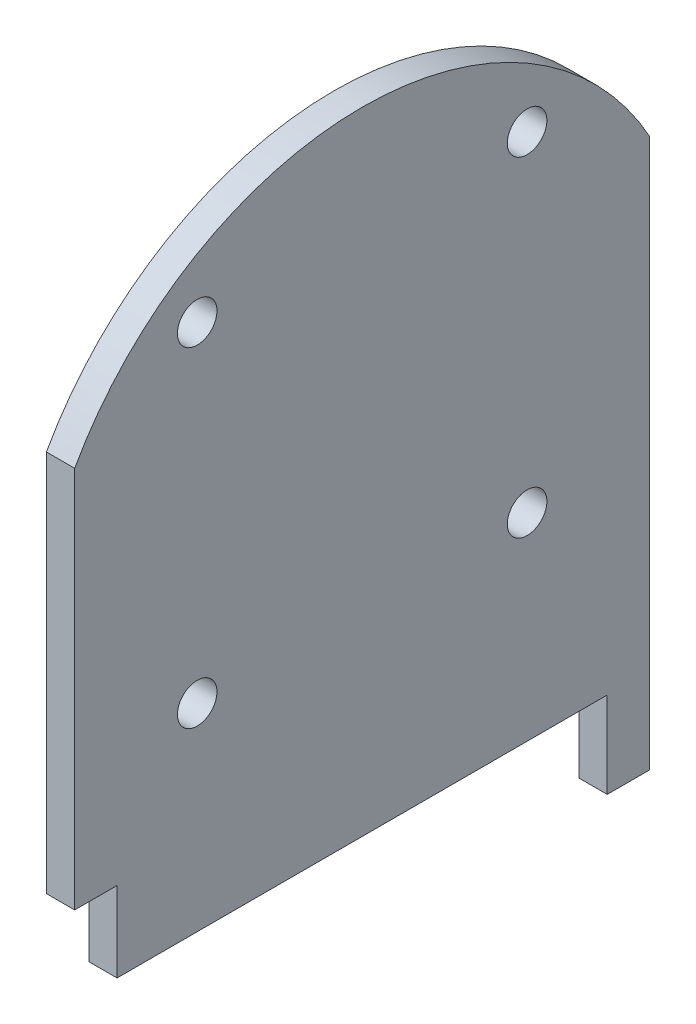
SolidWorks part; units mm, degrees
ref_plane "前视基准面" through (0, 0, 0) normal (0, 0, 1) x (1, 0, 0)
ref_plane "上视基准面" through (0, 0, 0) normal (0, 1, 0) x (1, 0, 0)
ref_plane "右视基准面" through (0, 0, 0) normal (1, 0, 0) x (0, 0, -1)
other "Configuration Table"
sketch "草图2" plane through (-116.6066, 0, 0) normal (-1, 0, 0) x (0, 0, 1)
  line L0 (1026.1543, -34.2835) -> (1026.1543, -63.7835) construction
  line L1 (1087.1543, -34.2835) -> (1087.1543, -63.7835) construction
  line L10 (1030.6543, -102.2835) -> (1082.6543, -102.2835)
  line L11 (1082.6543, -102.2835) -> (1082.6543, -93.7835)
  line L12 (1082.6543, -93.7835) -> (1087.1543, -93.7835)
  line L13 (1087.1543, -93.7835) -> (1087.1543, -63.7835)
  line L14 (1087.1543, -63.7835) -> (1087.1543, -34.2835)
  line L15 (1087.1543, -34.2835) -> (1026.1543, -34.2835)
  line L16 (1026.1543, -34.2835) -> (1026.1543, -63.7835)
  line L17 (1026.1543, -63.7835) -> (1026.1543, -93.7835)
  line L18 (1026.1543, -93.7835) -> (1030.6543, -93.7835)
  line L19 (1030.6543, -93.7835) -> (1030.6543, -102.2835)
  line L20 (1030.6543, -102.2835) -> (1082.6543, -102.2835)
  line L21 (1082.6543, -102.2835) -> (1082.6543, -93.7835)
  line L22 (1082.6543, -93.7835) -> (1087.1543, -93.7835)
  line L23 (1087.1543, -93.7835) -> (1087.1543, -63.7835)
  line L24 (1087.1543, -63.7835) -> (1087.1543, -53.2007)
  line L26 (1026.1543, -53.2007) -> (1026.1543, -63.7835)
  line L27 (1026.1543, -63.7835) -> (1026.1543, -111.4161)
  line L28 (1026.1543, -111.4161) -> (1030.6543, -111.4161)
  line L29 (1030.6543, -111.4161) -> (1030.6543, -102.2835)
  circle A0 centre (1074.1543, -81.2835) radius 2.1 construction
  circle A1 centre (1039.1543, -81.2835) radius 2.1 construction
  circle A2 centre (1074.1543, -46.2835) radius 2.1 construction
  circle A3 centre (1039.1543, -46.2835) radius 2.1 construction
  circle A4 centre (1074.1543, -81.2835) radius 2.1
  circle A5 centre (1039.1543, -81.2835) radius 2.1
  circle A6 centre (1074.1543, -46.2835) radius 2.1
  circle A7 centre (1039.1543, -46.2835) radius 2.1
  arc A8 (1026.1543, -53.2007) -> (1087.1543, -53.2007) centre (1056.6543, -70.1818) cw
  point P24 (1026.1543, -58.3927)
  point P26 (1087.1543, -58.3927)
  point P28 (1026.1543, -53.2007)
  point P31 (1087.1543, -53.2007)
  dimension "D1" = 0
extrude "凸台-拉伸1" add sketch "草图2" along normal blind 3
